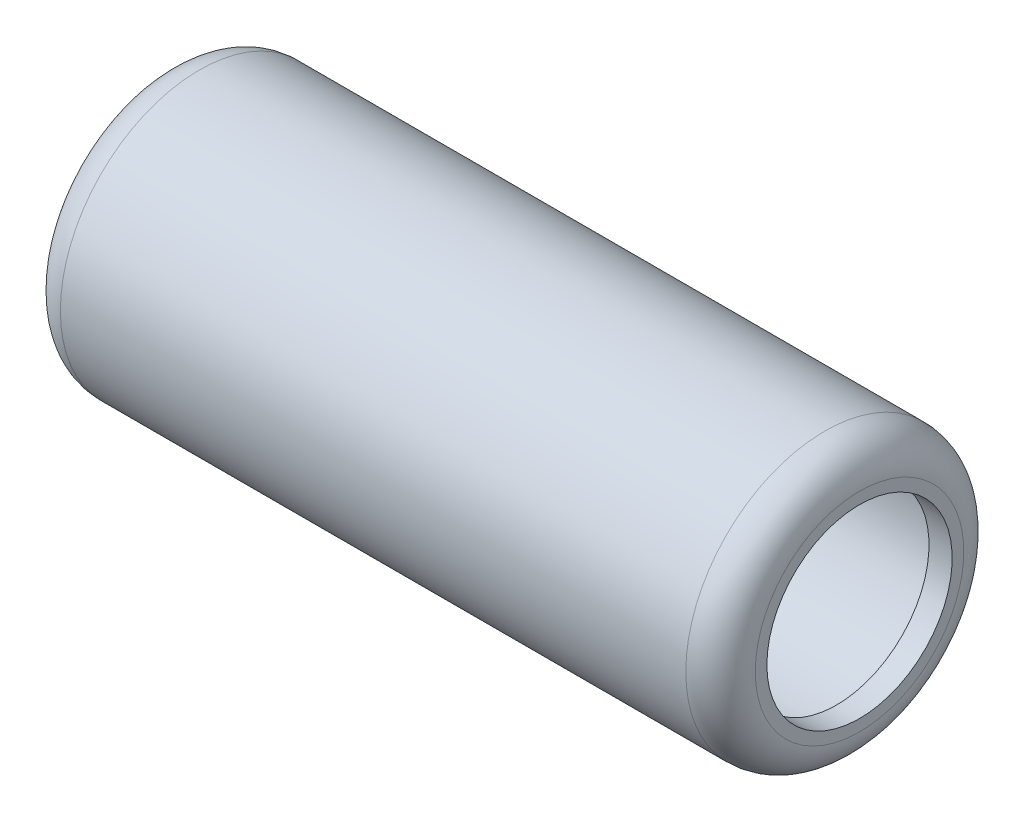
SolidWorks part; units mm, degrees
ref_plane "Plan1" through (0, 0, 0) normal (0, 0, 1) x (1, 0, 0)
ref_plane "Plan2" through (0, 0, 0) normal (0, 1, 0) x (1, 0, 0)
ref_plane "Plan3" through (0, 0, 0) normal (1, 0, 0) x (0, 0, -1)
sketch "Esquisse1" plane through (0, 0, 0) normal (0, 0, 1) x (1, 0, 0)
  line L0 (0, 0) -> (40, 0) construction
  line L1 (1.5, 6) -> (28.5, 6)
  line L2 (0, 4.5) -> (0, 4)
  line L3 (0, 4) -> (1, 4)
  line L4 (1, 4) -> (1, 4.5)
  line L5 (1.5, 5) -> (28.5, 5)
  line L6 (29, 4.5) -> (29, 4)
  line L7 (29, 4) -> (30, 4)
  line L8 (30, 4) -> (30, 4.5)
  arc A0 (1.5, 6) -> (0, 4.5) centre (1.5, 4.5) ccw
  arc A1 (28.5, 6) -> (30, 4.5) centre (28.5, 4.5) cw
  arc A2 (28.5, 5) -> (29, 4.5) centre (28.5, 4.5) cw
  arc A3 (1, 4.5) -> (1.5, 5) centre (1.5, 4.5) cw
  dimension "D3" = 1.5
  dimension "D5" = 0.5
  dimension "D1" = 1
  dimension "D2" = 0.5
  dimension "D4" = 1
  dimension "D6" = 6
  dimension "D7" = 30
revolve "Base-Révolution" add sketch "Esquisse1" angle 360 about L0
